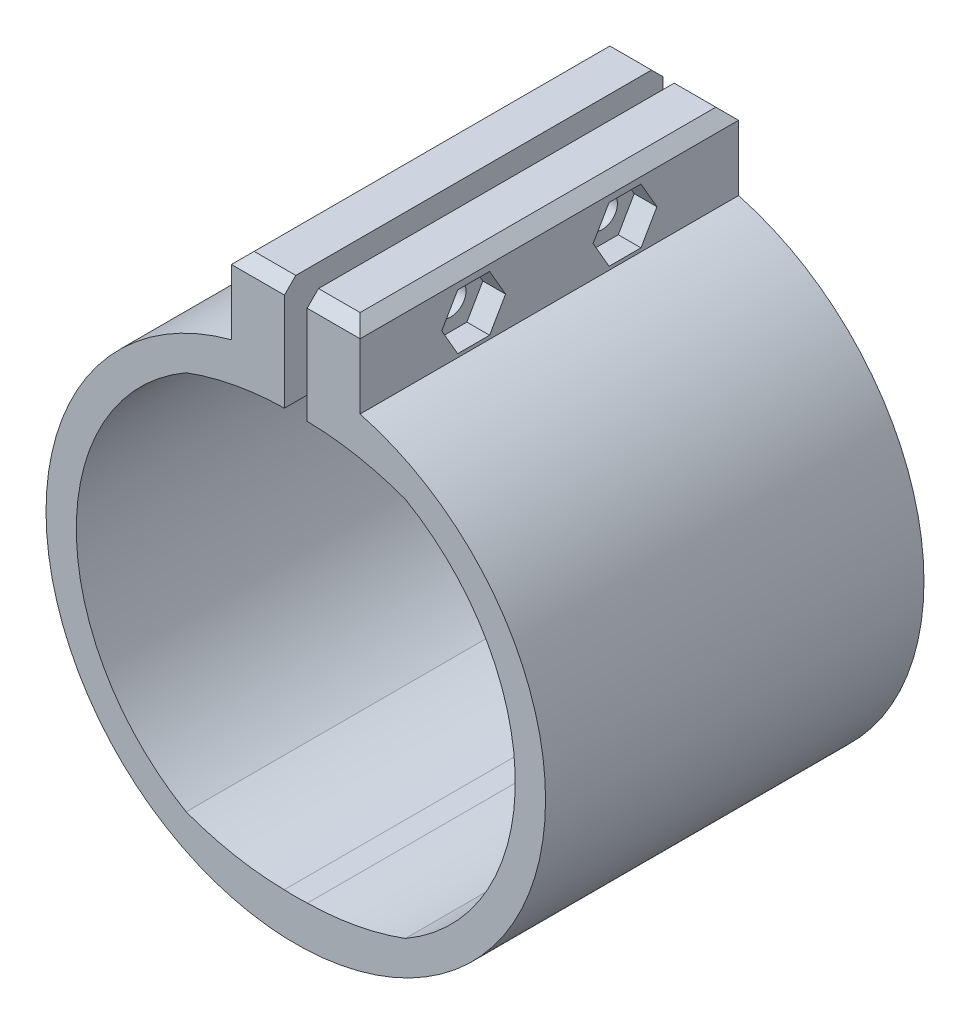
SolidWorks part; units mm, degrees
ref_plane "정면" through (0, 0, 0) normal (0, 0, 1) x (1, 0, 0)
ref_plane "윗면" through (0, 0, 0) normal (0, 1, 0) x (1, 0, 0)
ref_plane "우측면" through (0, 0, 0) normal (1, 0, 0) x (0, 0, -1)
sketch "스케치1" plane through (0, 0, 0) normal (0, 0, 1) x (1, 0, 0)
  line L0 (0, 27.6) -> (0, 0) construction
  line L1 (0, 0) -> (-56.4026, 0) construction
  line L2 (-1.5, 32.4654) -> (-1.5, 42)
  line L3 (-1.5, 42) -> (-8.5, 42)
  line L4 (-1.5, 32.4654) -> (-1.5, 27.5592)
  line L5 (-8.5, 42) -> (-8.5, 31.8865)
  line L6 (1.5, 32.4654) -> (1.5, 27.5592)
  line L7 (1.5, 32.4654) -> (1.5, 42)
  line L8 (1.5, 42) -> (8.5, 42)
  line L9 (8.5, 42) -> (8.5, 31.8865)
  arc A0 (-14.4858, 25.123) -> (-14.4858, -25.123) centre (0, 0) ccw
  arc A1 (-1.5288, -27.5576) -> (1.5288, -27.5576) centre (0, 0) ccw
  arc A2 (-1.5288, 27.5576) -> (-14.4858, 25.123) centre (-0.8913, -11.5297) ccw
  arc A3 (1.5288, 27.5576) -> (14.4858, 25.123) centre (0.8913, -11.5297) cw
  arc A4 (1.5288, -27.5576) -> (14.4858, -25.123) centre (0.8913, 11.5297) ccw
  arc A5 (-1.5288, -27.5576) -> (-14.4858, -25.123) centre (-0.8913, 11.5297) cw
  arc A6 (14.4858, -25.123) -> (14.4858, 25.123) centre (0, 0) ccw
  arc A7 (1.5288, 27.5576) -> (1.5, 27.5592) centre (0, 0) ccw
  arc A8 (-8.5, 31.8865) -> (8.5, 31.8865) centre (0, 0) ccw
  arc A9 (-1.5, 27.5592) -> (-1.5288, 27.5576) centre (0, 0) ccw
  point P3 (0, 29.8725)
  dimension "D1" = 58
  dimension "D2" = 55.2
  dimension "D3" = 66
  dimension "D4" = 3
  dimension "D5" = 1.5
  dimension "D6" = 7
  dimension "D7" = 42
extrude "보스-돌출1" add sketch "스케치1" along normal blind 50
sketch "스케치2" plane through (0, 0, 0) normal (1, 0, 0) x (0, 0, -1)
  line L0 (-25, 42) -> (-25, 36) construction
  line L1 (-50, 42) -> (0, 42) construction
  line L2 (-35, 36) -> (-15, 36) construction
  circle A0 centre (-35, 36) radius 2
  circle A1 centre (-15, 36) radius 2
  dimension "D1" = 4
  dimension "D2" = 4
  dimension "D3" = 20
  dimension "D4" = 6
extrude "컷-돌출1" cut sketch "스케치2" against normal through all both and the other way through all
sketch "스케치3" plane through (-8.5, 0, 0) normal (-1, 0, 0) x (0, 0, 1)
  circle A0 centre (15, 36) radius 3.5
  circle A1 centre (35, 36) radius 3.5
  dimension "D1" = 7
  dimension "D2" = 7
extrude "컷-돌출2" cut sketch "스케치3" against normal blind 2
sketch "스케치4" plane through (8.5, 0, 0) normal (1, 0, 0) x (0, 0, -1)
  line L1 (-30.7853, 36) -> (-32.8927, 39.65)
  line L2 (-32.8927, 39.65) -> (-37.1073, 39.65)
  line L3 (-37.1073, 39.65) -> (-39.2147, 36)
  line L4 (-39.2147, 36) -> (-37.1073, 32.35)
  line L5 (-37.1073, 32.35) -> (-32.8927, 32.35)
  line L6 (-32.8927, 32.35) -> (-30.7853, 36)
  line L7 (-10.7853, 36) -> (-12.8927, 39.65)
  line L8 (-12.8927, 39.65) -> (-17.1073, 39.65)
  line L9 (-17.1073, 39.65) -> (-19.2147, 36)
  line L10 (-19.2147, 36) -> (-17.1073, 32.35)
  line L11 (-17.1073, 32.35) -> (-12.8927, 32.35)
  line L12 (-12.8927, 32.35) -> (-10.7853, 36)
  circle A0 centre (-35, 36) radius 3.65 construction
  circle A1 centre (-15, 36) radius 3.65 construction
  dimension "D1" = 7.3
  dimension "D2" = 7.3
chamfer "모따기1" distance 1.5 angle 45 6 edges at (-5, 42, 0) (-8.5, 42, 25) (-5, 42, 50) (5, 42, 0) (8.5, 42, 25) (5, 42, 50)
extrude "컷-돌출3" cut sketch "스케치4" against normal blind 3
